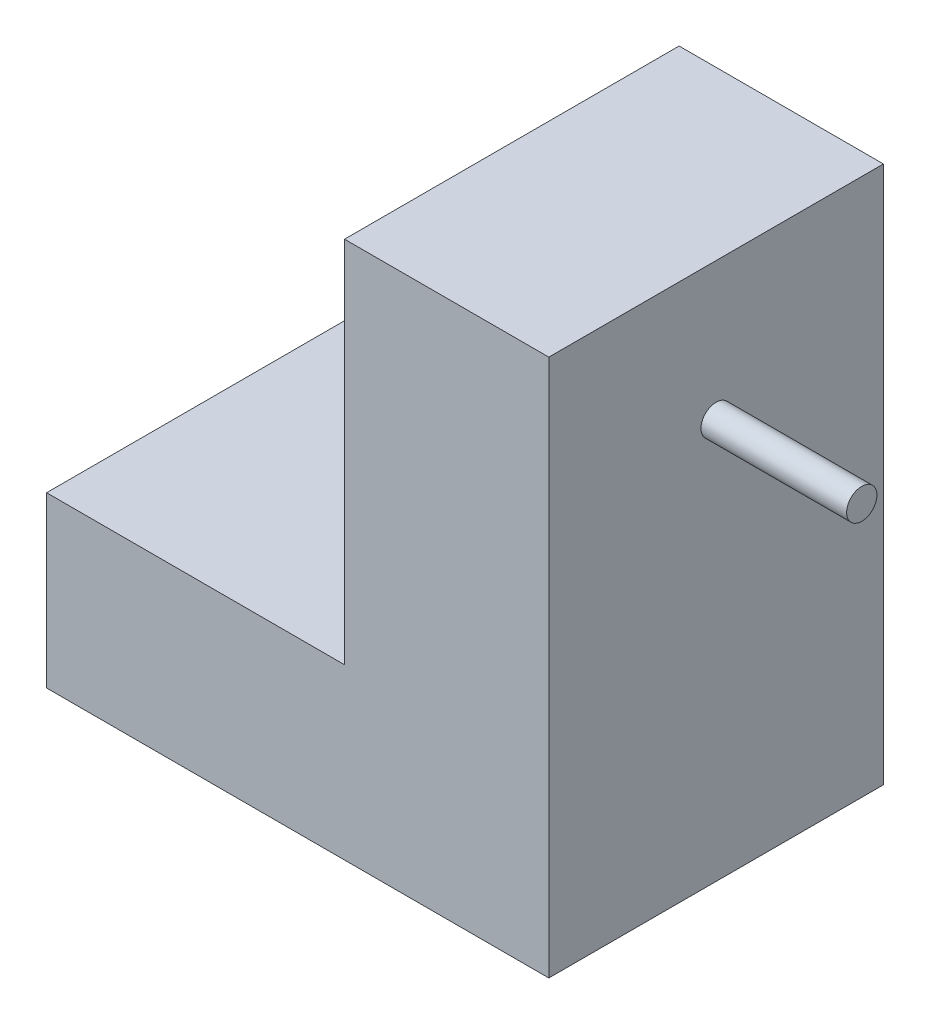
SolidWorks part; units mm, degrees
ref_plane "Front Plane" through (0, 0, 0) normal (0, 0, 1) x (1, 0, 0)
ref_plane "Top Plane" through (0, 0, 0) normal (0, 1, 0) x (1, 0, 0)
ref_plane "Right Plane" through (0, 0, 0) normal (1, 0, 0) x (0, 0, -1)
sketch "Sketch1" plane through (0, 0, 0) normal (0, 1, 0) x (1, 0, 0)
  line L1 (-17, -11.325) -> (17, -11.325)
  line L2 (-17, -11.325) -> (-17, 11.325)
  line L3 (-17, 11.325) -> (17, 11.325)
  line L4 (17, -11.325) -> (17, 11.325)
  line L5 (-17, -11.325) -> (17, 11.325) construction
  line L6 (-17, 11.325) -> (17, -11.325) construction
  point P0 (0, 0)
  dimension "D1" = 22.65
  dimension "D2" = 34
extrude "Boss-Extrude1" add sketch "Sketch1" along normal blind 11.45
sketch "Sketch2" plane through (0, 11.45, 0) normal (0, 1, 0) x (1, 0, 0)
  line L0 (-17, -11.325) -> (17, -11.325) construction
  line L1 (17, 11.325) -> (3.17, 11.325)
  line L2 (17, 11.325) -> (17, -11.325)
  line L3 (17, -11.325) -> (3.17, -11.325)
  line L4 (3.17, 11.325) -> (3.17, -11.325)
  dimension "D1" = 13.83
extrude "Boss-Extrude2" add sketch "Sketch2" along normal blind 24.95
sketch "Sketch5" plane through (17, 0, 0) normal (1, 0, 0) x (0, 0, -1)
  line L0 (-11.325, 0) -> (11.325, 0) construction
  circle A0 centre (0, 27.07) radius 1.025
  dimension "D1" = 2.05
  dimension "D2" = 27.07
extrude "Boss-Extrude3" add sketch "Sketch5" along normal blind 9.86
